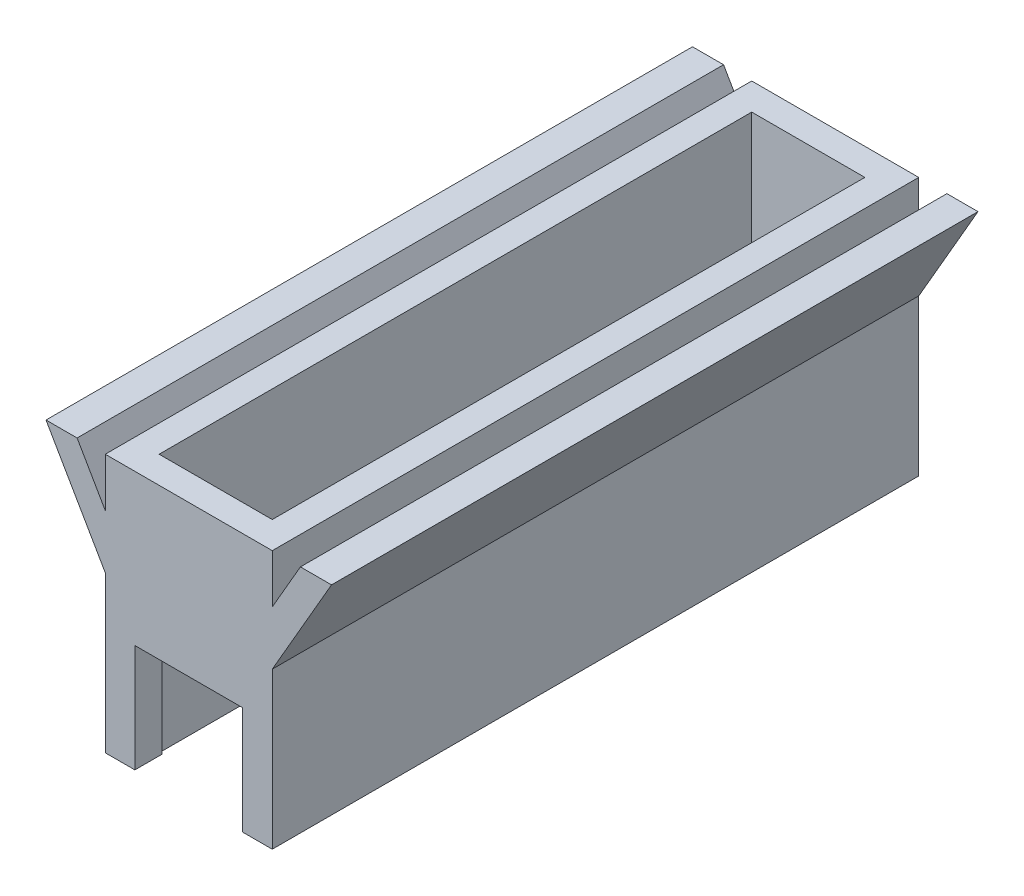
SolidWorks part; units mm, degrees
ref_plane "Front Plane" through (0, 0, 0) normal (0, 0, 1) x (1, 0, 0)
ref_plane "Top Plane" through (0, 0, 0) normal (0, 1, 0) x (1, 0, 0)
ref_plane "Right Plane" through (0, 0, 0) normal (1, 0, 0) x (0, 0, -1)
sketch "Sketch1" plane through (0, 0, 0) normal (0, 1, 0) x (1, 0, 0)
  line L1 (-6.7407, 4.992) -> (24.2593, 4.992)
  line L2 (-6.7407, 4.992) -> (-6.7407, -115.008)
  line L3 (-6.7407, -115.008) -> (24.2593, -115.008)
  line L4 (24.2593, 4.992) -> (24.2593, -115.008)
  line L8 (-1.7407, -0.008) -> (19.2593, -0.008)
  line L9 (19.2593, -0.008) -> (19.2593, -110.008)
  line L10 (-1.7407, -110.008) -> (19.2593, -110.008)
  line L11 (-1.7407, -0.008) -> (-1.7407, -110.008)
  dimension "D1" = 31
  dimension "D2" = 120
  dimension "D3" = 5
extrude "Boss-Extrude4" add sketch "Sketch1" along normal blind 48
sketch "Sketch6" plane through (0, 0, 115.008) normal (0, 0, 1) x (1, 0, 0)
  line L0 (-1.2407, 20) -> (-1.2407, 0)
  line L1 (-1.2407, 20) -> (18.7593, 20)
  line L2 (-1.2407, 0) -> (18.7593, 0)
  line L3 (18.7593, 20) -> (18.7593, 0)
  line L4 (-1.2407, 20) -> (18.7593, 0) construction
  line L5 (-1.2407, 0) -> (18.7593, 20) construction
  point P0 (8.7593, 0)
  point P1 (8.7593, 10)
  dimension "D1" = 15.5
  dimension "D2" = 20
  dimension "D3" = 20
extrude "Cut-Extrude3" cut sketch "Sketch6" against normal blind 136 contours L0 L1 L3 L2
sketch "Sketch7" plane through (0, 0, 115.008) normal (0, 0, 1) x (1, 0, 0)
  line L0 (24.2593, 28.9474) -> (35.2593, 48)
  line L1 (24.2593, 48) -> (24.2593, 0) construction
  line L2 (-17.7407, 48) -> (35.2593, 48)
  line L3 (-6.7407, 28.9474) -> (-6.7407, 38.9474)
  line L4 (24.2593, 38.9474) -> (29.4858, 48)
  line L6 (19.9292, 31.4474) -> (26.599, 43) construction
  line L7 (8.7593, 48) -> (8.7593, 39.5819) construction
  line L8 (-6.7407, 38.9474) -> (-11.9672, 48)
  line L9 (-6.7407, 28.9474) -> (-17.7407, 48)
  line L10 (24.2593, 28.9474) -> (24.2593, 38.9474)
  line L11 (-17.7407, 43) -> (26.599, 43) construction
  point P7 (8.7593, 48)
  line M9 (24.2593, 0) -> (24.2593, 48)
  line M11 (-6.7407, 48) -> (-6.7407, 0)
  dimension "D1" = 30
  dimension "D2" = 26.5
  dimension "D3" = 5
extrude "Boss-Extrude5" add sketch "Sketch7" against normal blind 120 contours L9 L8 L2 M11 | L4 L0 L2 M9
